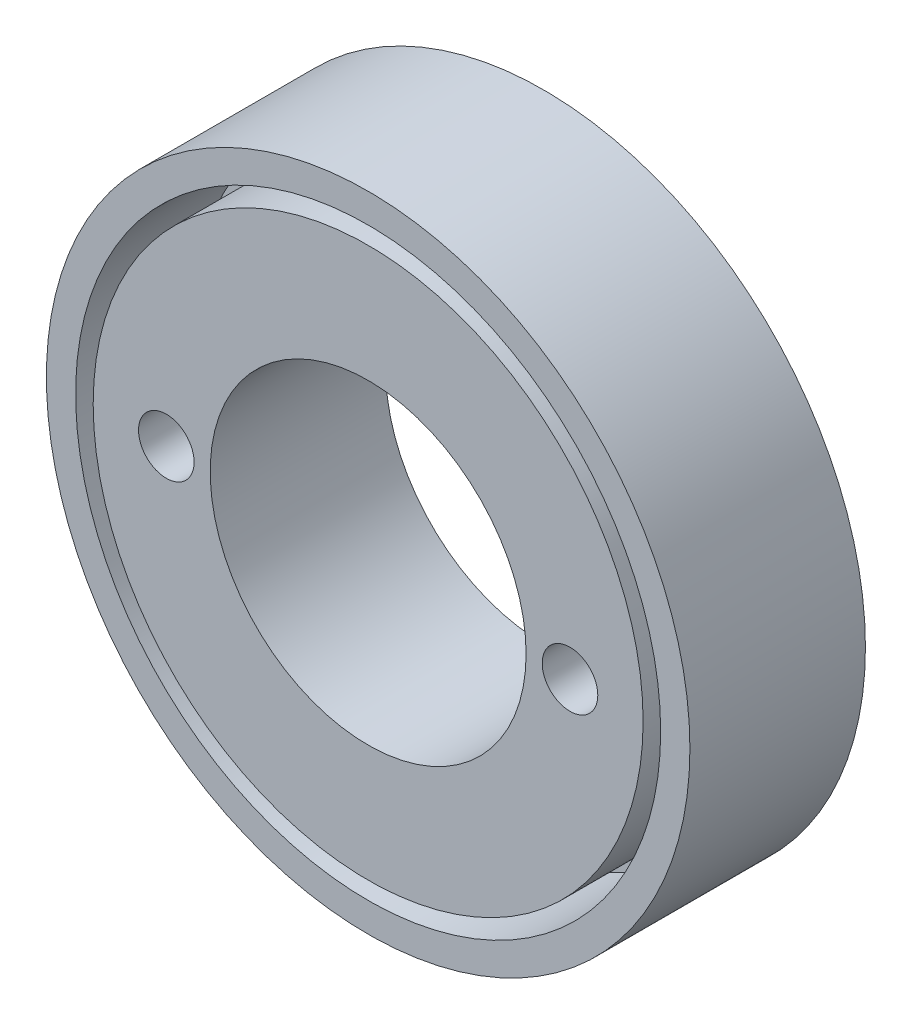
SolidWorks part; units mm, degrees
ref_plane "Front Plane" through (0, 0, 0) normal (0, 0, 1) x (1, 0, 0)
ref_plane "Top Plane" through (0, 0, 0) normal (0, 1, 0) x (1, 0, 0)
ref_plane "Right Plane" through (0, 0, 0) normal (1, 0, 0) x (0, 0, -1)
sketch "Sketch1" plane through (0, 0, 0) normal (0, 0, 1) x (1, 0, 0)
  circle A0 centre (0, 0) radius 55
  circle A1 centre (0, 0) radius 27
  dimension "D1" = 110
  dimension "D2" = 54
extrude "Boss-Extrude1" add sketch "Sketch1" along normal blind 10
sketch "Sketch2" plane through (0, 0, 10) normal (0, 0, 1) x (1, 0, 0)
  line L0 (0, -5.5) -> (0, 5.5) construction
  circle A0 centre (0, 0) radius 50
  circle A1 centre (0, 0) radius 47
  circle A2 centre (-34.5, 0) radius 4.75
  circle A3 centre (34.5, 0) radius 4.75
  circle A4 centre (0, 0) radius 27
  circle A5 centre (0, 0) radius 55
  circle M4 centre (0, 0) radius 55
  circle M5 centre (0, 0) radius 27
  dimension "D1" = 100
  dimension "D2" = 3
  dimension "D3" = 9.5
  dimension "D4" = 34.5
extrude "Boss-Extrude4" add sketch "Sketch2" along normal blind 20 contours A1 A2 A3 M5 | A0 M4
